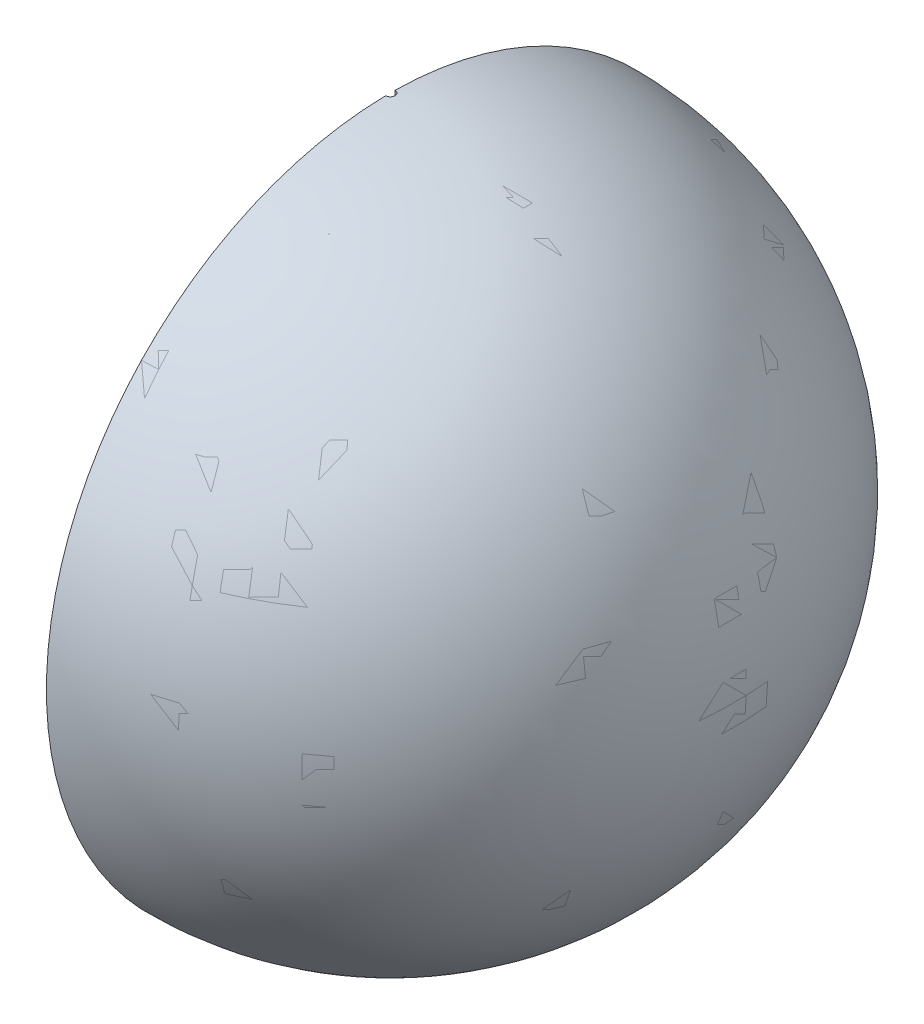
SolidWorks part; units mm, degrees
ref_plane "Front Plane" through (0, 0, 0) normal (0, 0, 1) x (1, 0, 0)
ref_plane "Top Plane" through (0, 0, 0) normal (0, 1, 0) x (1, 0, 0)
ref_plane "Right Plane" through (0, 0, 0) normal (1, 0, 0) x (0, 0, -1)
other "Configuration Table"
sketch "Sketch2" plane through (0, 0, 0) normal (1, 0, 0) x (0, 0, -1)
  line L0 (0, 44.4297) -> (0, -44.4297) construction
  line L1 (0, 40.0051) -> (0.0993, -40.005)
  arc A0 (0, 40.0051) -> (0.0993, -40.005) centre (0, 0) cw
revolve "Revolve1" add sketch "Sketch2" angle 180 about L1
sketch "Sketch3" plane through (0, 0, 0) normal (0, 1, 0) x (1, 0, 0)
  circle A0 centre (0, 0) radius 0.5419
extrude "Cut-Extrude1" cut sketch "Sketch3" against normal mid plane 83
surface "Surface-Offset1" parameters "D1"=0
sketch "Sketch4" plane through (0, 0, 0) normal (1, 0, 0) x (0, 0, -1)
  line L0 (16.2018, -18.7801) -> (38.3159, -44.261)
curve "Curve1"
sketch "Sketch5" plane through (0, 0, 0) normal (1, 0, 0) x (0, 0, -1)
  line L0 (19.5348, 17.1136) -> (32.9949, 28.7791)
curve "Curve2"
sketch "Sketch6" plane through (0, 0, 0) normal (1, 0, 0) x (0, 0, -1)
  line L0 (-17.5126, 19.1647) -> (-30.0754, 33.0094)
curve "Curve3"
sketch "Sketch7" plane through (0, 0, 0) normal (1, 0, 0) x (0, 0, -1)
  line L0 (-17.6408, -16.729) -> (-32.5111, -30.5737)
curve "Curve4"
sketch "Sketch9" plane through (0, 0, 0) normal (1, 0, 0) x (0, 0, -1)
  line L0 (0, 25.7025) -> (0, 42.4956)
curve "Curve5"
sketch "Sketch10" plane through (0, 0, 0) normal (1, 0, 0) x (0, 0, -1)
  line L0 (24.5343, 0) -> (41.8402, 0)
curve "Curve6"
sketch "Sketch11" plane through (0, 0, 0) normal (1, 0, 0) x (0, 0, -1)
  line L0 (0, -24.2923) -> (0, -42.2392)
curve "Curve7"
sketch "Sketch12" plane through (0, 0, 0) normal (1, 0, 0) x (0, 0, -1)
  line L0 (-25.2042, 0) -> (-42.51, 0)
curve "Curve8"
